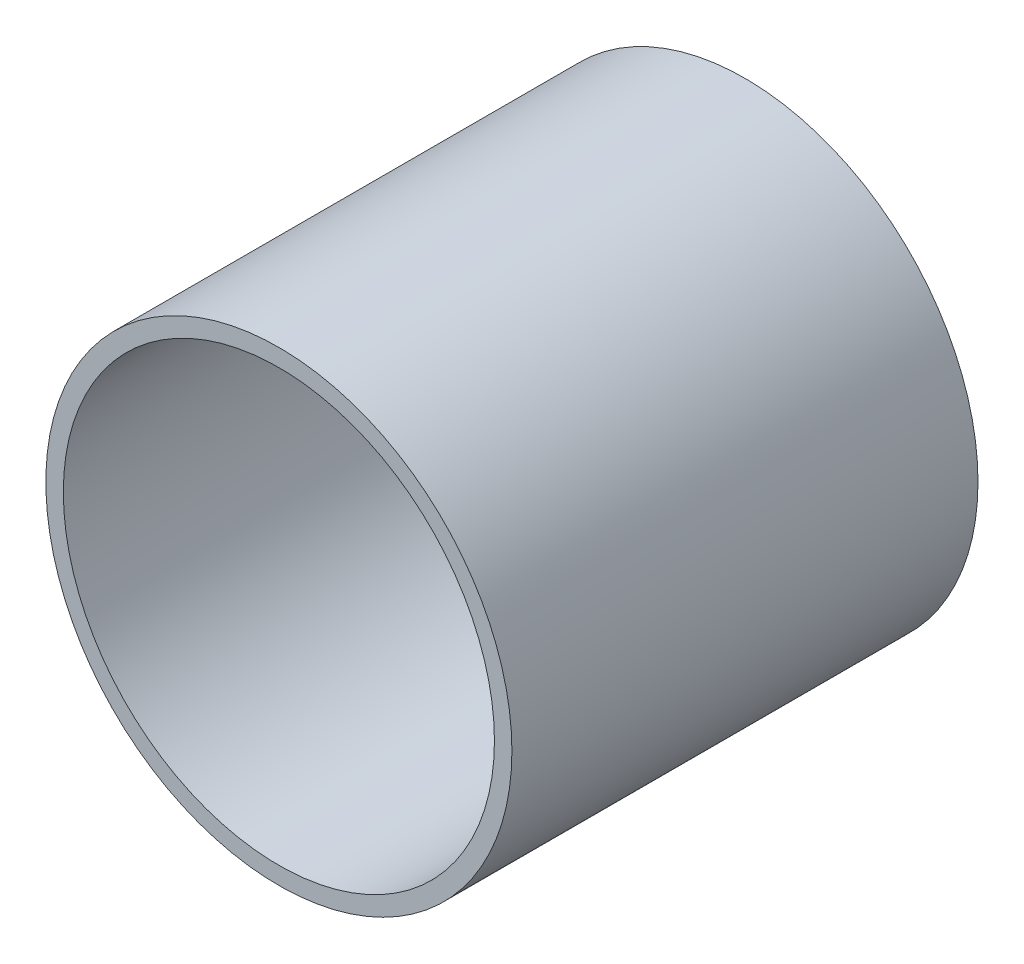
SolidWorks part; units mm, degrees
ref_plane "前视基准面" through (0, 0, 0) normal (0, 0, 1) x (1, 0, 0)
ref_plane "上视基准面" through (0, 0, 0) normal (0, 1, 0) x (1, 0, 0)
ref_plane "右视基准面" through (0, 0, 0) normal (1, 0, 0) x (0, 0, -1)
sketch "草图1" plane through (0, 0, 0) normal (0, 0, 1) x (1, 0, 0)
  circle A0 centre (0, 0) radius 20
  circle A1 centre (0, 0) radius 18.5
  dimension "D1" = 40
  dimension "D2" = 37
extrude "凸台-拉伸1" add sketch "草图1" along normal mid plane 40 from offset 0
